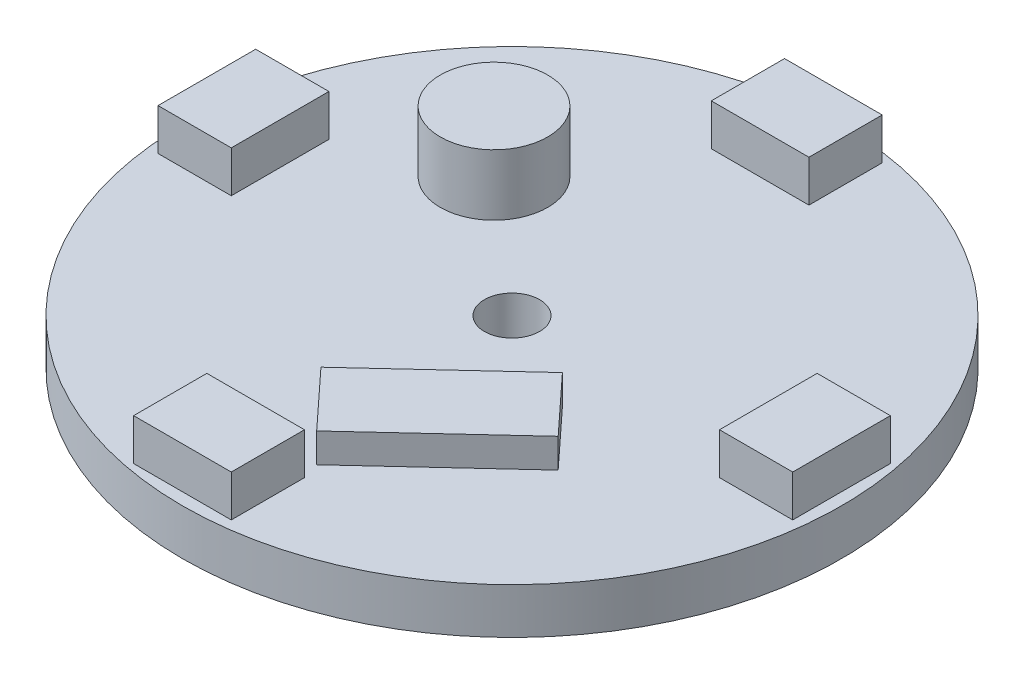
SolidWorks part; units mm, degrees
ref_plane "Front Plane" through (0, 0, 0) normal (0, 0, 1) x (1, 0, 0)
ref_plane "Top Plane" through (0, 0, 0) normal (0, 1, 0) x (1, 0, 0)
ref_plane "Right Plane" through (0, 0, 0) normal (1, 0, 0) x (0, 0, -1)
sketch "Sketch1" plane through (0, 0, 0) normal (0, 1, 0) x (1, 0, 0)
  circle A0 centre (-9.2709, 8.8179) radius 17.145
  circle A1 centre (-9.2709, 8.8179) radius 1.4362
  dimension "D1" = 34.29
extrude "Boss-Extrude1" add sketch "Sketch1" along normal blind 2.3813
sketch "Sketch2" plane through (0, 0, 0) normal (0, -1, 0) x (-1, 0, 0)
sketch "Sketch3" plane through (0, 2.3813, 0) normal (0, 1, 0) x (1, 0, 0)
  circle A0 centre (-16.0076, 14.6186) radius 2.794
  circle A1 centre (-9.2709, 8.8179) radius 1.4362 construction
  dimension "D1" = 5.588
  dimension "D2" = 8.89
extrude "Boss-Extrude2" add sketch "Sketch3" along normal blind 3.175
sketch "Sketch4" plane through (0, 2.3813, 0) normal (0, 1, 0) x (1, 0, 0)
  line L0 (-10.3916, -0.0012) -> (-3.8672, 6.0374)
  line L1 (-3.8672, 6.0374) -> (-1.1067, 3.0548)
  line L2 (-1.1067, 3.0548) -> (-7.6311, -2.9838)
  line L3 (-7.6311, -2.9838) -> (-10.0465, -0.374)
  line L4 (-10.0465, -0.374) -> (-10.3916, -0.0012)
  circle A0 centre (-9.2709, 8.8179) radius 1.4362 construction
  dimension "D3" = 8.89
  dimension "D1" = 8.89
  dimension "D2" = 4.064
extrude "Boss-Extrude3" add sketch "Sketch4" along normal blind 1.524
sketch "Sketch5" plane through (0, 2.3813, 0) normal (0, 1, 0) x (1, 0, 0)
  line L0 (-12.4459, -3.8821) -> (-7.3659, -3.8821)
  line L1 (-11.6028, 25.3279) -> (-6.5228, 25.3279)
  line L2 (-11.6028, 25.3279) -> (-11.6028, 21.5179)
  line L3 (-11.6028, 21.5179) -> (-6.5228, 21.5179)
  line L4 (-6.5228, 25.3279) -> (-6.5228, 21.5179)
  line L5 (-12.4459, -3.8821) -> (-12.4459, -7.6921)
  line L6 (-12.4459, -7.6921) -> (-7.3659, -7.6921)
  line L7 (-7.3659, -3.8821) -> (-7.3659, -7.6921)
  line L9 (-25.7809, 11.9929) -> (-21.9709, 11.9929)
  line L10 (-25.7809, 11.9929) -> (-25.7809, 6.9129)
  line L11 (-25.7809, 6.9129) -> (-21.9709, 6.9129)
  line L12 (-21.9709, 11.9929) -> (-21.9709, 6.9129)
  line L13 (3.4291, 11.9929) -> (7.2391, 11.9929)
  line L14 (3.4291, 11.9929) -> (3.4291, 6.9129)
  line L15 (3.4291, 6.9129) -> (7.2391, 6.9129)
  line L16 (7.2391, 11.9929) -> (7.2391, 6.9129)
  dimension "D1" = 5.08
  dimension "D4" = 5.08
  dimension "D2" = 5.08
  dimension "D3" = 5.08
extrude "Boss-Extrude4" add sketch "Sketch5" along normal blind 2.159
